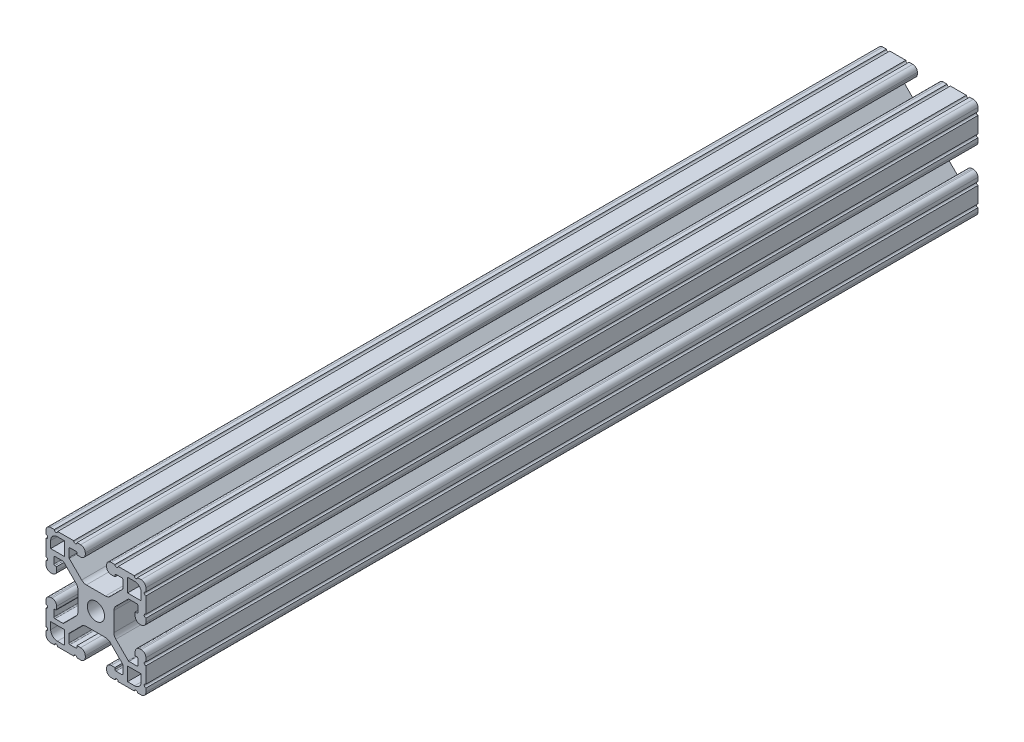
SolidWorks part; units mm, degrees
ref_plane "Front Plane" through (0, 0, 0) normal (0, 0, 1) x (1, 0, 0)
ref_plane "Top Plane" through (0, 0, 0) normal (0, 1, 0) x (1, 0, 0)
ref_plane "Right Plane" through (0, 0, 0) normal (1, 0, 0) x (0, 0, -1)
sketch "Sketch1" plane through (0, 0, 0) normal (0, 0, 1) x (1, 0, 0)
  line L0 (0, -19.05) -> (0, 19.05) construction
  line L1 (19.05, 0) -> (-19.05, 0) construction
  line L2 (4.064, 19.05) -> (-4.064, 19.05) construction
  line L3 (0, -6.858) -> (0, 6.858) construction
  line L4 (-4.064, 19.05) -> (-4.064, 14.986) construction
  line L5 (19.05, -10.287) -> (19.05, 10.287) construction
  line L6 (0, -3.302) -> (0, 3.302) construction
  point P4 (0, 0)
  point P8 (0, 0)
  point P11 (0, 19.05)
  point P14 (0, 0)
  point P18 (19.05, 0)
  point P21 (0, 0)
  dimension "Rail Width" = 38.1
  dimension "Rail Height" = 38.1
  dimension "T-Slot Width" = 8.128
  dimension "Thickness" = 4.064
  dimension "Opening Width" = 20.574
  dimension "Center Hole Diameter" = 6.604
  dimension "Slot Depth" = 12.192
sketch "Sketch2" plane through (0, 0, 0) normal (1, 0, 0) x (0, 0, -1)
  line L0 (-158.75, 0) -> (158.75, 0) construction
  line L1 (0, 19.05) -> (0, -19.05) construction
  line L2 (-25.4, 19.05) -> (25.4, 19.05) construction
  line L4 (3048, -19.05) -> (-3048, -19.05) construction
  point P0 (107.95, 0)
  point P3 (-107.95, 0)
  point P4 (0, 0)
  dimension "D1" = 50.8
  dimension "Rep Length" = 317.5
  dimension "D2" = 50.8
  dimension "Length Range [Min]" = 50.8
  dimension "Length Range [Max]" = 6096
sketch "Sketch3" plane through (0, 0, 0) normal (0, 0, 1) x (1, 0, 0)
  line L1 (19.05, -19.05) -> (-19.05, -19.05)
  line L2 (19.05, -19.05) -> (19.05, 19.05)
  line L3 (19.05, 19.05) -> (-19.05, 19.05)
  line L4 (-19.05, -19.05) -> (-19.05, 19.05)
  line L5 (19.05, -19.05) -> (-19.05, 19.05) construction
  line L6 (19.05, 19.05) -> (-19.05, -19.05) construction
  point P0 (0, 0)
extrude "Boss-Extrude1" add sketch "Sketch3" along normal up to vertex (158.75 mm away) and the other way up to vertex (158.75 mm away) up to point (0, 0, 158.75) other way up to point (0, 0, -158.75)
sketch "Sketch4" plane through (0, 0, 158.75) normal (0, 0, 1) x (1, 0, 0)
  line L4 (4.064, 14.986) -> (4.064, 19.05)
  line L5 (7.239, 14.986) -> (4.064, 14.986)
  line L6 (19.05, 0) -> (-19.05, 0) construction
  line L7 (4.7027, 6.858) -> (-4.7027, 6.858)
  line L8 (-4.7027, 6.858) -> (-10.287, 12.4423)
  line L37 (-19.05, 19.05) -> (-19.05, -19.05) construction
  line L38 (-19.05, -19.05) -> (19.05, -19.05) construction
  line L39 (-10.287, 12.4423) -> (-10.287, 16.002)
  line L40 (-10.287, 16.002) -> (-7.239, 16.002)
  line L41 (-7.239, 16.002) -> (-7.239, 14.986)
  line L42 (-7.239, 14.986) -> (-4.064, 14.986)
  line L43 (-4.064, 14.986) -> (-4.064, 19.05)
  line L44 (-4.064, 19.05) -> (4.064, 19.05)
  line L45 (0, 19.05) -> (0, 0) construction
  line L46 (-19.05, 19.05) -> (0, 0) construction
  line L47 (7.239, 16.002) -> (7.239, 14.986)
  line L48 (10.287, 16.002) -> (7.239, 16.002)
  line L49 (10.287, 12.4423) -> (10.287, 16.002)
  line L50 (4.7027, 6.858) -> (10.287, 12.4423)
  line L51 (-19.05, 0) -> (19.05, 0) construction
  line L52 (4.7027, -6.858) -> (10.287, -12.4423)
  line L53 (10.287, -12.4423) -> (10.287, -16.002)
  line L54 (10.287, -16.002) -> (7.239, -16.002)
  line L55 (7.239, -16.002) -> (7.239, -14.986)
  line L56 (-4.064, -19.05) -> (4.064, -19.05)
  line L57 (-4.064, -14.986) -> (-4.064, -19.05)
  line L58 (-7.239, -14.986) -> (-4.064, -14.986)
  line L59 (-7.239, -16.002) -> (-7.239, -14.986)
  line L60 (-10.287, -16.002) -> (-7.239, -16.002)
  line L61 (-10.287, -12.4423) -> (-10.287, -16.002)
  line L62 (-4.7027, -6.858) -> (-10.287, -12.4423)
  line L63 (4.7027, -6.858) -> (-4.7027, -6.858)
  line L64 (7.239, -14.986) -> (4.064, -14.986)
  line L65 (4.064, -14.986) -> (4.064, -19.05)
  line L66 (-6.858, -4.7027) -> (-12.4423, -10.287)
  line L67 (-12.4423, -10.287) -> (-16.002, -10.287)
  line L68 (-16.002, -10.287) -> (-16.002, -7.239)
  line L69 (-16.002, -7.239) -> (-14.986, -7.239)
  line L70 (-19.05, 4.064) -> (-19.05, -4.064)
  line L71 (-14.986, 4.064) -> (-19.05, 4.064)
  line L72 (-14.986, 7.239) -> (-14.986, 4.064)
  line L73 (-16.002, 7.239) -> (-14.986, 7.239)
  line L74 (-16.002, 10.287) -> (-16.002, 7.239)
  line L75 (-12.4423, 10.287) -> (-16.002, 10.287)
  line L76 (-6.858, 4.7027) -> (-12.4423, 10.287)
  line L77 (-6.858, -4.7027) -> (-6.858, 4.7027)
  line L78 (-14.986, -7.239) -> (-14.986, -4.064)
  line L79 (-14.986, -4.064) -> (-19.05, -4.064)
  line L80 (14.986, -4.064) -> (19.05, -4.064)
  line L81 (14.986, -7.239) -> (14.986, -4.064)
  line L82 (6.858, -4.7027) -> (6.858, 4.7027)
  line L83 (6.858, 4.7027) -> (12.4423, 10.287)
  line L84 (12.4423, 10.287) -> (16.002, 10.287)
  line L85 (16.002, 10.287) -> (16.002, 7.239)
  line L86 (16.002, 7.239) -> (14.986, 7.239)
  line L87 (14.986, 7.239) -> (14.986, 4.064)
  line L88 (14.986, 4.064) -> (19.05, 4.064)
  line L89 (19.05, 4.064) -> (19.05, -4.064)
  line L90 (16.002, -7.239) -> (14.986, -7.239)
  line L91 (16.002, -10.287) -> (16.002, -7.239)
  line L92 (12.4423, -10.287) -> (16.002, -10.287)
  line L93 (6.858, -4.7027) -> (12.4423, -10.287)
  line L94 (19.05, -19.05) -> (19.05, 19.05) construction
  line L95 (12.065, 17.272) -> (17.272, 17.272)
  line L96 (12.065, 17.272) -> (12.065, 12.065)
  line L97 (12.065, 12.065) -> (17.272, 12.065)
  line L98 (17.272, 17.272) -> (17.272, 12.065)
  line L99 (19.05, 19.05) -> (-19.05, 19.05) construction
  line L100 (17.272, -17.272) -> (17.272, -12.065)
  line L101 (12.065, -17.272) -> (17.272, -17.272)
  line L102 (12.065, -17.272) -> (12.065, -12.065)
  line L103 (12.065, -12.065) -> (17.272, -12.065)
  line L104 (-17.272, 17.272) -> (-17.272, 12.065)
  line L105 (-12.065, 12.065) -> (-17.272, 12.065)
  line L106 (-12.065, 17.272) -> (-12.065, 12.065)
  line L107 (-12.065, 17.272) -> (-17.272, 17.272)
  line L108 (-12.065, -12.065) -> (-17.272, -12.065)
  line L109 (-12.065, -17.272) -> (-12.065, -12.065)
  line L110 (-12.065, -17.272) -> (-17.272, -17.272)
  line L111 (-17.272, -17.272) -> (-17.272, -12.065)
  circle A5 centre (0, 0) radius 3.302
  point P21 (0, 6.858)
  point P23 (0, -6.858)
  point P38 (-6.858, 0)
  point P53 (6.858, 0)
  dimension "D1" = 20.574
  dimension "D2" = 3.048
  dimension "D3" = 3.048
  dimension "D4" = 3.048
  dimension "D5" = 1.778
  dimension "D6" = 1.778
  dimension "D7" = 1.778
extrude "Cut-Extrude1" cut sketch "Sketch4" against normal through all
sketch "Sketch5" plane through (0, 0, 158.75) normal (0, 0, 1) x (1, 0, 0)
  line L4 (-4.064, 19.05) -> (-19.05, 19.05) construction
  line L26 (-19.05, 19.05) -> (-19.05, 4.064) construction
  line L27 (-15.875, 19.05) -> (-14.605, 19.05)
  line L28 (-8.509, 19.05) -> (-7.239, 19.05)
  line L29 (-19.05, 15.875) -> (-19.05, 14.605)
  line L30 (-19.05, 8.509) -> (-19.05, 7.239)
  line L31 (8.509, 19.05) -> (7.239, 19.05)
  line L32 (15.875, 19.05) -> (14.605, 19.05)
  line L33 (19.05, 15.875) -> (19.05, 14.605)
  line L34 (19.05, 8.509) -> (19.05, 7.239)
  line L35 (19.05, -8.509) -> (19.05, -7.239)
  line L36 (19.05, -15.875) -> (19.05, -14.605)
  line L37 (15.875, -19.05) -> (14.605, -19.05)
  line L38 (8.509, -19.05) -> (7.239, -19.05)
  line L39 (-8.509, -19.05) -> (-7.239, -19.05)
  line L40 (-15.875, -19.05) -> (-14.605, -19.05)
  line L41 (-19.05, -15.875) -> (-19.05, -14.605)
  line L42 (-19.05, -8.509) -> (-19.05, -7.239)
  line L43 (19.05, 19.05) -> (4.064, 19.05) construction
  line L44 (19.05, 4.064) -> (19.05, 19.05) construction
  line L48 (-14.986, 4.064) -> (-19.05, 4.064) construction
  line L49 (-4.064, 14.986) -> (-4.064, 19.05) construction
  arc A8 (-15.875, 19.05) -> (-14.605, 19.05) centre (-15.24, 19.05) ccw
  arc A9 (-8.509, 19.05) -> (-7.239, 19.05) centre (-7.874, 19.05) ccw
  arc A10 (-19.05, 14.605) -> (-19.05, 15.875) centre (-19.05, 15.24) ccw
  arc A11 (-19.05, 7.239) -> (-19.05, 8.509) centre (-19.05, 7.874) ccw
  arc A12 (7.239, 19.05) -> (8.509, 19.05) centre (7.874, 19.05) ccw
  arc A13 (14.605, 19.05) -> (15.875, 19.05) centre (15.24, 19.05) ccw
  arc A14 (19.05, 15.875) -> (19.05, 14.605) centre (19.05, 15.24) ccw
  arc A15 (19.05, 8.509) -> (19.05, 7.239) centre (19.05, 7.874) ccw
  arc A16 (19.05, -7.239) -> (19.05, -8.509) centre (19.05, -7.874) ccw
  arc A17 (19.05, -14.605) -> (19.05, -15.875) centre (19.05, -15.24) ccw
  arc A18 (15.875, -19.05) -> (14.605, -19.05) centre (15.24, -19.05) ccw
  arc A19 (8.509, -19.05) -> (7.239, -19.05) centre (7.874, -19.05) ccw
  arc A20 (-7.239, -19.05) -> (-8.509, -19.05) centre (-7.874, -19.05) ccw
  arc A21 (-14.605, -19.05) -> (-15.875, -19.05) centre (-15.24, -19.05) ccw
  arc A22 (-19.05, -15.875) -> (-19.05, -14.605) centre (-19.05, -15.24) ccw
  arc A23 (-19.05, -8.509) -> (-19.05, -7.239) centre (-19.05, -7.874) ccw
  dimension "D2" = 0.635
  dimension "D4" = 3.81
  dimension "D5" = 3.81
  dimension "D1" = 3.81
  dimension "D3" = 3.81
  dimension "D7" = 4
extrude "Cut-Extrude2" cut sketch "Sketch5" against normal through all
fillet "Fillet1" radius 2.54 12 edges at (-6.858, 4.7027, 0) (-6.858, -4.7027, 0) (4.7027, -6.858, 0) (-4.7027, -6.858, 0) (6.858, -4.7027, 0) (6.858, 4.7027, 0) (4.7027, 6.858, 0) (-4.7027, 6.858, 0) (-17.272, 17.272, 0) (17.272, 17.272, 0) (17.272, -17.272, 0) (-17.272, -17.272, 0)
fillet "Fillet2" radius 1.778 20 edges at (19.05, -19.05, 0) (19.05, 19.05, 0) (-19.05, -19.05, 0) (-19.05, 19.05, 0) (-14.986, 4.064, 0) (-19.05, 4.064, 0) (-19.05, -4.064, 0) (-14.986, -4.064, 0) (-4.064, -19.05, 0) (-4.064, -14.986, 0) (4.064, -14.986, 0) (4.064, -19.05, 0) (19.05, -4.064, 0) (14.986, -4.064, 0) (19.05, 4.064, 0) (14.986, 4.064, 0) (4.064, 14.986, 0) (4.064, 19.05, 0) (-4.064, 19.05, 0) (-4.064, 14.986, 0)
fillet "Fillet3" radius 0.3969 24 edges at (-14.986, -7.239, 0) (-16.002, -10.287, 0) (-12.4423, -10.287, 0) (-12.4423, 10.287, 0) (-16.002, 7.239, 0) (-16.002, 10.287, 0) (-10.287, 12.4423, 0) (-7.239, 16.002, 0) (-10.287, 16.002, 0) (10.287, 16.002, 0) (7.239, 16.002, 0) (10.287, 12.4423, 0) (16.002, 10.287, 0) (12.4423, 10.287, 0) (16.002, 7.239, 0) (16.002, -7.239, 0) (16.002, -10.287, 0) (12.4423, -10.287, 0) (10.287, -12.4423, 0) (10.287, -16.002, 0) (7.239, -16.002, 0) (-7.239, -16.002, 0) (-10.287, -12.4423, 0) (-10.287, -16.002, 0)
equation "\"D4@Sketch5\"=\"D3@Sketch5\""
equation "\"D5@Sketch5\"=\"D4@Sketch5\""
equation "\"D1@Sketch4\"=\"Opening Width@Sketch1\""
